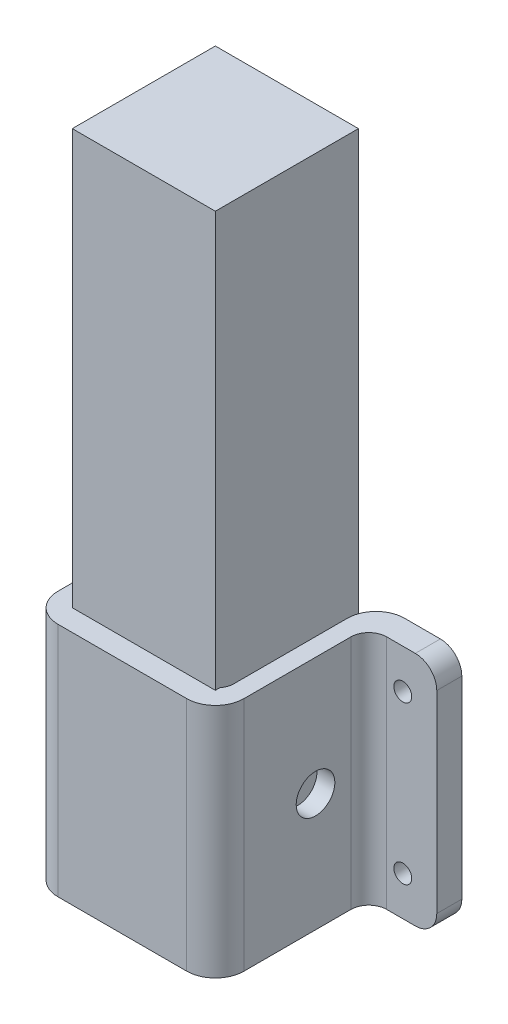
SolidWorks part; units mm, degrees
ref_plane "Front Plane" through (0, 0, 0) normal (0, 0, 1) x (1, 0, 0)
ref_plane "Top Plane" through (0, 0, 0) normal (0, 1, 0) x (1, 0, 0)
ref_plane "Right Plane" through (0, 0, 0) normal (1, 0, 0) x (0, 0, -1)
sketch "Sketch1" plane through (0, 0, 0) normal (0, 0, 1) x (1, 0, 0)
  line L1 (0, 0) -> (20, 0)
  line L2 (0, 0) -> (0, 91)
  line L3 (0, 91) -> (20, 91)
  line L4 (20, 0) -> (20, 91)
  dimension "D1" = 20
extrude "rod" add sketch "Sketch1" against normal blind 20
ref_plane "Plane1" through (10, 0, 0) normal (1, 0, 0) x (0, 0, -1)
sketch "Sketch2" plane through (0, 0, 0) normal (0, 0, 1) x (1, 0, 0)
  line L0 (-3, 33) -> (23, 33)
  line L1 (10, -11) -> (10, 11) construction
  line L2 (23, 33) -> (23, 0)
  line L3 (23, 0) -> (-3, 0)
  line L4 (0, 0) -> (20, 0) construction
  line L5 (10, 33) -> (10, 0) construction
  line L6 (-3, 33) -> (-3, 0)
  dimension "D1" = 33
sketch "Sketch4" plane through (0, 0, 0) normal (0, 0, 1) x (1, 0, 0)
  line L5 (23, 0) -> (23, 33)
  line L6 (23, 33) -> (20.5, 33)
  line L7 (-3, 33) -> (23, 33) construction
  line L8 (20.5, 33) -> (20.5, 0)
  line L9 (23, 0) -> (-3, 0) construction
  line L10 (20.5, 0) -> (23, 0)
  line L11 (10, 33) -> (10, 0) construction
  line L12 (-0.5, 33) -> (-0.5, 0)
  line L13 (-3, 33) -> (-0.5, 33)
  line L14 (-3, 0) -> (-3, 33)
  line L15 (-0.5, 0) -> (-3, 0)
extrude "Boss-Extrude3" add sketch "Sketch2" along normal blind 3 separate body contours L2 L3 L6 L0
extrude "Boss-Extrude4" add sketch "Sketch4" against normal blind 20.2
ref_plane "Plane2" through (0, 0, -20.2) normal (0, 0, 1) x (1, 0, 0)
sketch "Sketch5" plane through (0, 0, -20.2) normal (0, 0, 1) x (1, 0, 0)
  line L0 (20.5, 33) -> (32.5, 33)
  line L1 (32.5, 33) -> (32.5, 0)
  line L2 (32.5, 0) -> (20.5, 0)
  line L3 (20.5, 0) -> (20.5, 33)
  line L4 (-0.5, 0) -> (-0.5, 33) construction
  line L6 (-3, 33) -> (-3, 0) construction
  line L7 (-12.5, 0) -> (-0.5, 0)
  line L8 (-12.5, 33) -> (-12.5, 0)
  line L9 (-0.5, 33) -> (-12.5, 33)
  line L10 (-0.5, 0) -> (-0.5, 33)
  point P9 (20.5, 16.5)
  point P10 (-0.5, 16.5)
  point P21 (-3, 16.5)
  dimension "D1" = 33
  dimension "D2" = 12
  dimension "D3" = 12
extrude "Boss-Extrude5" add sketch "Sketch5" against normal blind 1.75 and the other way blind 1.75
sketch "Sketch8" plane through (0, 0, -18.45) normal (0, 0, 1) x (1, 0, 0)
  line L0 (23, 33) -> (27.75, 33) construction
  line L1 (32.5, 33) -> (23, 33) construction
  circle A0 centre (27.75, 27.5) radius 1.25
  circle A1 centre (27.75, 5.5) radius 1.25
  dimension "D1" = 2.5
  dimension "D3" = 22
  dimension "D2" = 5.5
extrude "Cut-Extrude1" cut sketch "Sketch8" against normal up to next (3.5 mm away) contours A0 | A1
ref_plane "Vertical Plane" through (10, 0, 0) normal (1, 0, 0) x (0, 0, -1)
mirror "Mirror1" about plane through (10, 0, 0) normal (1, 0, 0) of "Cut-Extrude1"
fillet "Fillet1" radius 2.5 2 edges at (-3, 16.5, -18.45) (23, 16.5, -18.45)
fillet "Fillet2" radius 4 2 edges at (-3, 16.5, 3) (23, 16.5, 3)
fillet "Fillet3" radius 2 2 edges at (20.5, 16.5, 0) (-0.5, 16.5, 0)
fillet "Fillet4" radius 4 2 edges at (20.5, 16.5, -21.95) (-0.5, 16.5, -21.95)
sketch "Sketch9" plane through (-3, 0, 0) normal (-1, 0, 0) x (0, 0, 1)
  line L0 (-1, 0) -> (-1, 33) construction
  line L3 (-1, 16.5) -> (-11, 16.5) construction
  circle A0 centre (-11, 16.5) radius 2.7
  point P3 (-1, 16.5)
  dimension "D1" = 10
  dimension "D2" = 5.4
extrude "Side Extrude" cut sketch "Sketch9" against normal up to next (2.5 mm away) contours A0
mirror "Mirror2" about plane through (10, 0, 0) normal (1, 0, 0) of "Side Extrude"
fillet "Fillet5" radius 3 4 edges at (32.5, 0, -20.2) (32.5, 33, -20.2) (-12.5, 0, -20.2) (-12.5, 33, -20.2)
